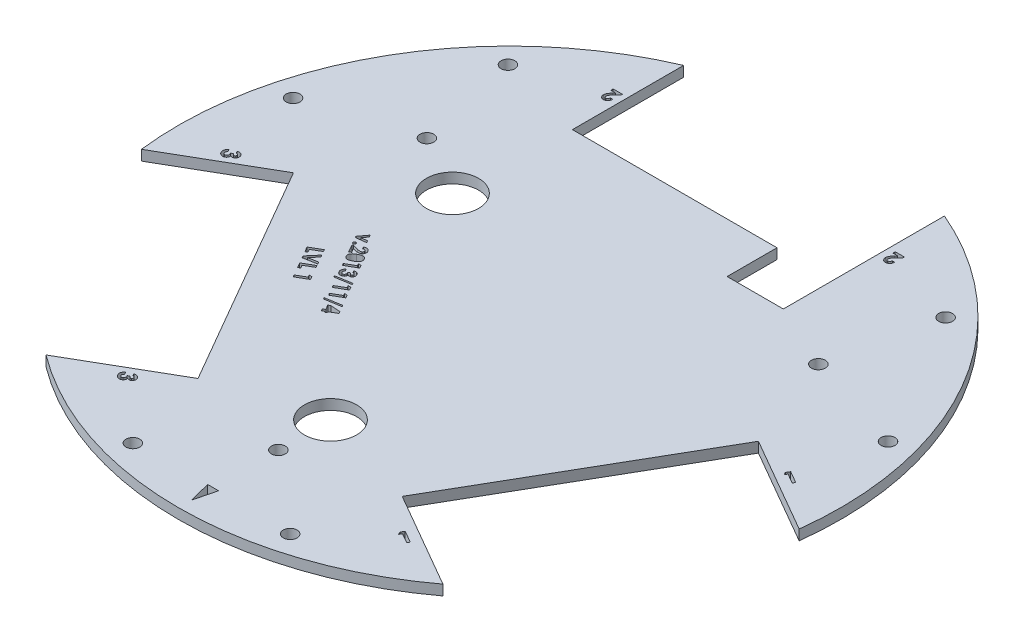
SolidWorks part; units mm, degrees
ref_plane "Front" through (0, 0, 0) normal (0, 0, 1) x (1, 0, 0)
ref_plane "Top" through (0, 0, 0) normal (0, 1, 0) x (1, 0, 0)
ref_plane "Right" through (0, 0, 0) normal (1, 0, 0) x (0, 0, -1)
sketch "Sketch1" plane through (0, 0, 0) normal (0, 1, 0) x (1, 0, 0)
  line L0 (-30, 70.046) -> (-30, 44.446)
  line L1 (-30, 44.446) -> (30, 44.446)
  line L2 (30, 44.446) -> (30, 70.046)
  line L3 (23.4914, -48.2038) -> (45.6616, -61.0038)
  line L4 (53.4914, 3.7578) -> (23.4914, -48.2038)
  line L5 (75.6616, -9.0422) -> (53.4914, 3.7578)
  line L6 (0, 0) -> (0, 50000) construction
  line L7 (0, 0) -> (50000, 0) construction
  line L8 (-53.4914, 3.7578) -> (-75.6616, -9.0422)
  line L9 (-23.4914, -48.2038) -> (-53.4914, 3.7578)
  line L10 (-45.6616, -61.0038) -> (-23.4914, -48.2038)
  line L11 (0, 0) -> (30, 44.446) construction
  line L12 (0, 0) -> (23.4914, -48.2038) construction
  line L13 (-30, 57.246) -> (-40.1827, 57.246) construction
  line L14 (30, 57.246) -> (40.1827, 57.246) construction
  line L15 (34.5765, -54.6038) -> (29.4851, -63.4222) construction
  line L16 (64.5765, -2.6422) -> (69.6678, 6.1762) construction
  line L17 (-64.5765, -2.6422) -> (-69.6678, 6.1762) construction
  line L18 (-34.5765, -54.6038) -> (-29.4851, -63.4222) construction
  line L19 (-42.791, -5.8838) -> (-26.491, -34.1162) construction
  arc A0 (-30, 70.046) -> (-75.6616, -9.0422) centre (0, 0) ccw
  arc A1 (75.6616, -9.0422) -> (30, 70.046) centre (0, 0) ccw
  arc A2 (-45.6616, -61.0038) -> (45.6616, -61.0038) centre (0, 0) ccw
  text T0 "<b>1 </b>"
  text T1 "<b> 1</b>"
  text T2 "<b>2 </b>"
  text T3 "<b> 2</b>"
  text T4 "<b>3 </b>"
  text T5 "<b> 3</b>"
  point P7 (38.4914, -22.223)
  point P43 (0, 0)
  dimension "D1" = 25.6
  dimension "D2" = 40
  dimension "D3" = 60
  dimension "D4" = 76.2
  dimension "D7" = 53.6232
  dimension "D5" = 3
  dimension "D6" = 120
  dimension "D8" = 32.6
  dimension "D10" = 13.7
  dimension "D9" = 3
extrude "Boss-Extrude1" add sketch "Sketch1" along normal blind 2.3622
sketch "Sketch2" plane through (0, 2.3622, 0) normal (0, 1, 0) x (1, 0, 0)
  line L0 (-18.1, -68.58) -> (18.1, -68.58) construction
  line L1 (0, 50000) -> (0, -50000) construction
  line L2 (-50000, 0) -> (50000, 0) construction
  line L3 (45.0333, 26) -> (0, 0) construction
  line L4 (-45.0333, 26) -> (0, 0) construction
  line L5 (68.442, 18.6149) -> (50.342, 49.9651) construction
  line L6 (-50.342, 49.9651) -> (-68.442, 18.6149) construction
  circle A0 centre (18.1, -68.58) radius 1.59
  circle A1 centre (-50.342, 49.9651) radius 1.59
  circle A2 centre (-18.1, -68.58) radius 1.59
  circle A3 centre (-68.442, 18.6149) radius 1.59
  circle A4 centre (68.442, 18.6149) radius 1.59
  circle A5 centre (50.342, 49.9651) radius 1.59
  circle A6 centre (45.0333, 26) radius 1.59
  circle A7 centre (0, -53.21) radius 1.59
  circle A8 centre (-45.0333, 26) radius 1.59
  circle A9 centre (0, -52) radius 1.59 [skipped]
  point P19 (0, 0)
  point P27 (0, 0)
  dimension "D1" = 18.1
  dimension "D3" = 68.58
  dimension "D4" = 3
  dimension "D5" = 3.18
  dimension "D6" = 3.18
  dimension "D10" = 52
  dimension "D12" = 53.21
  dimension "D2" = 36.2
  dimension "D7" = 52
  dimension "D8" = 30
  dimension "D11" = 30
  dimension "D9" = 3
extrude "Structure Mounting Holes" cut sketch "Sketch2" against normal blind 10
sketch "Sketch4" plane through (0, 2.3622, 0) normal (0, 1, 0) x (1, 0, 0)
  circle A0 centre (0, -41.2058) radius 6
  circle A2 centre (-31.0953, 17.9529) radius 6
extrude "Cable Holes" cut sketch "Sketch4" against normal blind 10
sketch "Sketch8" plane through (0, 2.3622, 0) normal (0, 1, 0) x (1, 0, 0)
  line L0 (-34.1308, -0.8838) -> (-16.0308, -32.2339) construction
  line L1 (30, 45.5436) -> (17.0703, 45.5436)
  line L2 (30, 45.5436) -> (30, 32.9727)
  line L3 (30, 32.9727) -> (17.0703, 32.9727)
  line L4 (17.0703, 45.5436) -> (17.0703, 32.9727)
  line L5 (-53.4914, 3.7578) -> (-23.4914, -48.2038) construction
  line L6 (-75.6616, -9.0422) -> (-53.4914, 3.7578) construction
  text T0 "<b>v.2013/11/4</b>\r\n<b>     LVL 1 </b>"
  dimension "D1" = 12.9297
  dimension "D2" = 12.5709
  dimension "D3" = 17.0703
  dimension "D4" = 32.9727
  dimension "D5" = 36.2
  dimension "D6" = 13.7
  dimension "D7" = 30
extrude "Cut-Extrude6" cut sketch "Sketch8" against normal blind 2.54
delete or keep bodies "Body-Delete1" type delete bodies bodies 113 114
sketch "Sketch9" plane through (0, 2.3622, 0) normal (0, 1, 0) x (1, 0, 0)
  line L0 (0, 0) -> (50000, 0) construction
  line L1 (0, 0) -> (0, 50000) construction
  line L2 (-1.25, -68.21) -> (1.25, -68.21)
  line L3 (1.25, -68.21) -> (0, -73.21)
  line L4 (0, -73.21) -> (-1.25, -68.21)
  dimension "D1" = 2.5
  dimension "D2" = 5
  dimension "D3" = 68.21
  dimension "D4" = 1.25
extrude "Cut-Extrude7" cut sketch "Sketch9" against normal blind 10
